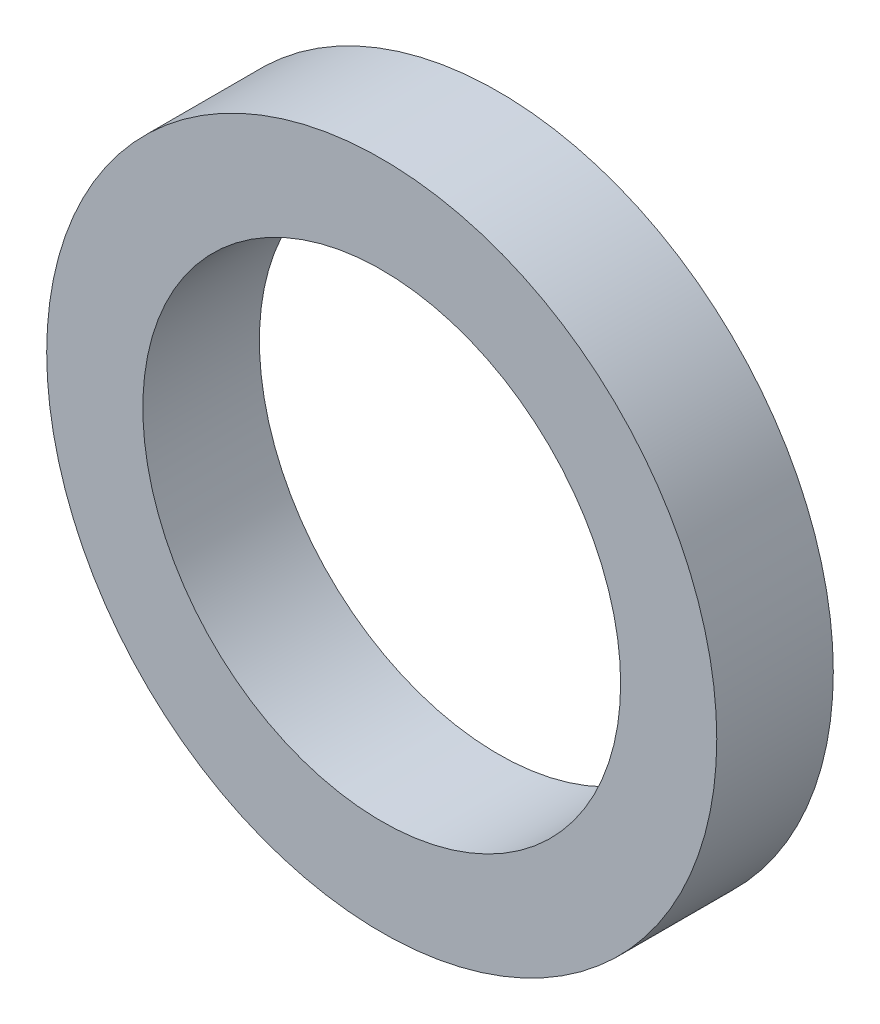
SolidWorks part; units mm, degrees
ref_plane "Front Plane" through (0, 0, 0) normal (0, 0, 1) x (1, 0, 0)
ref_plane "Top Plane" through (0, 0, 0) normal (0, 1, 0) x (1, 0, 0)
ref_plane "Right Plane" through (0, 0, 0) normal (1, 0, 0) x (0, 0, -1)
sketch "Sketch1" plane through (0, 0, 0) normal (0, 0, 1) x (1, 0, 0)
  circle A0 centre (0, 0) radius 5.75
  circle A1 centre (0, 0) radius 4.1
extrude "Spacer" add sketch "Sketch1" along normal blind 2
